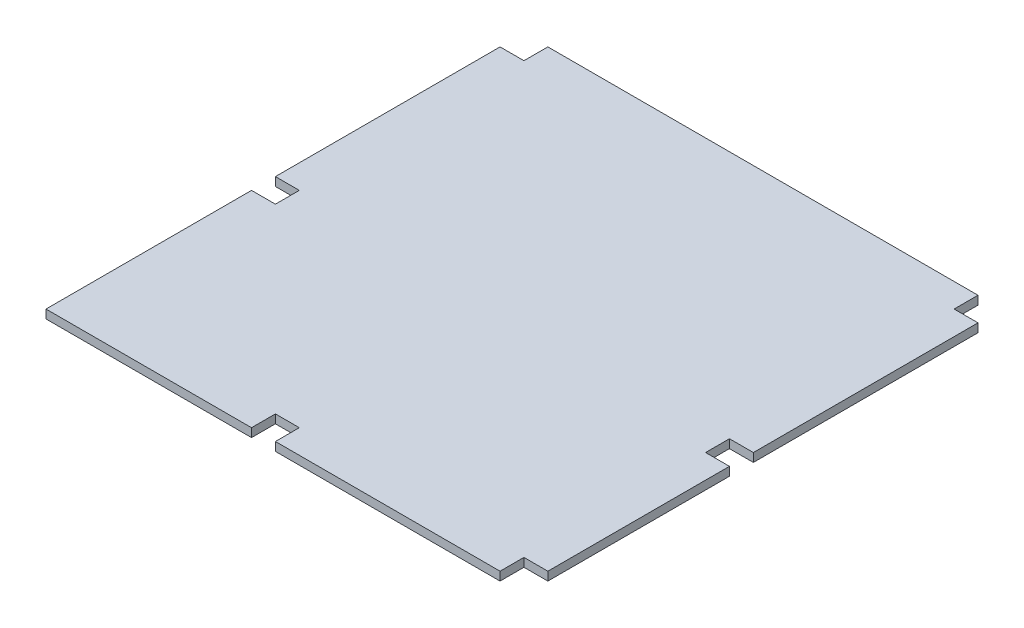
SolidWorks part; units mm, degrees
material "Teak"
ref_plane "Front Plane" through (0, 0, 0) normal (0, 0, 1) x (1, 0, 0)
ref_plane "Top Plane" through (0, 0, 0) normal (0, 1, 0) x (1, 0, 0)
ref_plane "Right Plane" through (0, 0, 0) normal (1, 0, 0) x (0, 0, -1)
sketch "Sketch1" plane through (0, 0, 0) normal (0, 1, 0) x (1, 0, 0)
  line L0 (0, 300) -> (0, 770)
  line L1 (0, -180) -> (430, -180)
  line L2 (0, -180) -> (0, 250)
  line L3 (50, 820) -> (950, 820)
  line L4 (1000, -130) -> (1000, 250)
  line L5 (0, 250) -> (50, 250)
  line L7 (0, 300) -> (50, 300)
  line L8 (50, 250) -> (50, 300)
  line L9 (480, -180) -> (950, -180)
  line L12 (0, 770) -> (50, 770)
  line L13 (50, 820) -> (50, 770)
  line L16 (1000, 770) -> (950, 770)
  line L17 (950, 820) -> (950, 770)
  line L20 (1000, -130) -> (950, -130)
  line L21 (950, -180) -> (950, -130)
  line L23 (430, -180) -> (430, -130)
  line L24 (430, -130) -> (480, -130)
  line L25 (480, -180) -> (480, -130)
  line L26 (500, 590.5919) -> (500, 117.6624) construction
  line L27 (1000, 250) -> (950, 250)
  line L28 (950, 250) -> (950, 300)
  line L29 (1000, 300) -> (950, 300)
  line L30 (1000, 300) -> (1000, 770)
  dimension "D3" = 50
  dimension "D4" = 50
  dimension "D5" = 430
  dimension "D6" = 50
  dimension "D7" = 50
  dimension "D8" = 50
  dimension "D9" = 50
  dimension "D10" = 50
  dimension "D11" = 50
  dimension "D12" = 50
  dimension "D13" = 50
  dimension "D14" = 430
extrude "Boss-Extrude1" add sketch "Sketch1" along normal blind 18 contours L1 L23 L24 L25 L9 L21 L20 L4 L27 L28 L29 L30 L16 L17 L3 L13 L12 L0 L7 L8 L5 L2
